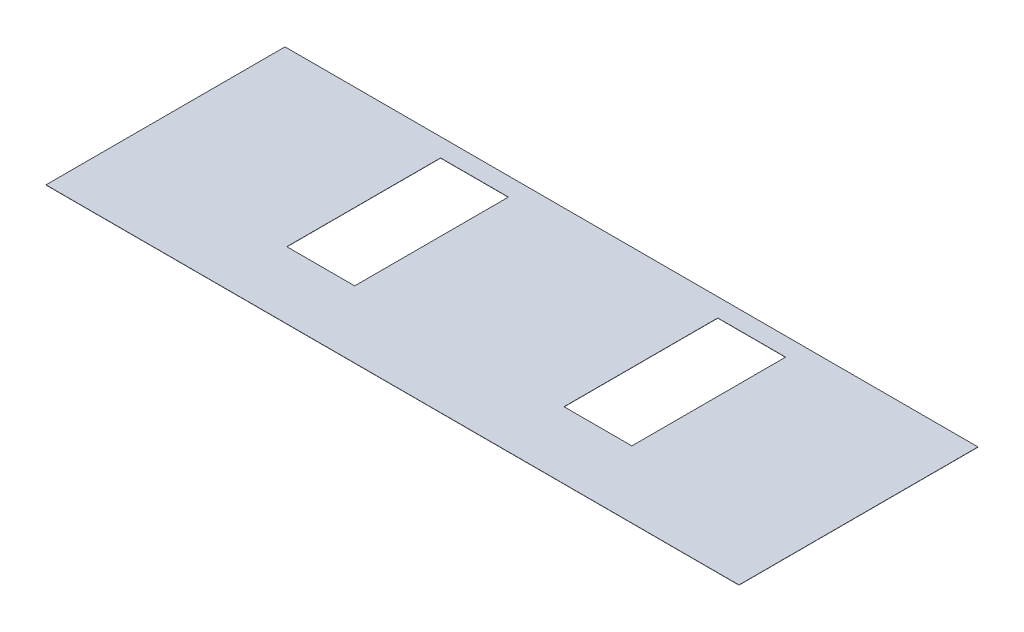
SolidWorks part; units mm, degrees
material "PE High Density Film"
ref_plane "Front Plane" through (0, 0, 0) normal (0, 0, 1) x (1, 0, 0)
ref_plane "Top Plane" through (0, 0, 0) normal (0, 1, 0) x (1, 0, 0)
ref_plane "Right Plane" through (0, 0, 0) normal (1, 0, 0) x (0, 0, -1)
sketch "Sketch1" plane through (0, 0, 0) normal (0, 1, 0) x (1, 0, 0)
  line L1 (-3048, -1051.306) -> (3048, -1051.306)
  line L2 (-3048, -1051.306) -> (-3048, 1051.306)
  line L3 (-3048, 1051.306) -> (3048, 1051.306)
  line L4 (3048, -1051.306) -> (3048, 1051.306)
  line L5 (-3048, -1051.306) -> (3048, 1051.306) construction
  line L6 (-3048, 1051.306) -> (3048, -1051.306) construction
  point P0 (0, 0)
  dimension "D1" = 2102.612
  dimension "D2" = 6096
extrude "Boss-Extrude1" add sketch "Sketch1" along normal blind 1.5875
sketch "Sketch2" plane through (0, 1.5875, 0) normal (0, 1, 0) x (1, 0, 0)
  line L0 (-3048, 1051.306) -> (-1828.8, 1051.306) construction
  line L1 (3048, 1051.306) -> (-3048, 1051.306) construction
  line L2 (-1828.8, 1051.306) -> (-609.6, 1051.306) construction
  line L3 (-609.6, 1051.306) -> (609.6, 1051.306) construction
  line L4 (609.6, 1051.306) -> (1828.8, 1051.306) construction
  line L5 (1828.8, 1051.306) -> (3048, 1051.306) construction
  line L6 (-1219.2, 1051.306) -> (-1219.2, -252.9133) construction
  line L7 (1219.2, 1051.306) -> (1219.2, -252.9133) construction
  line L9 (-1517.65, 889.381) -> (-920.75, 889.381)
  line L10 (-1517.65, 889.381) -> (-1517.65, -463.169)
  line L11 (-1517.65, -463.169) -> (-920.75, -463.169)
  line L12 (-920.75, 889.381) -> (-920.75, -463.169)
  line L13 (-1517.65, 889.381) -> (-920.75, -463.169) construction
  line L14 (-1517.65, -463.169) -> (-920.75, 889.381) construction
  line L15 (920.75, 889.381) -> (1517.65, 889.381)
  line L16 (920.75, 889.381) -> (920.75, -463.169)
  line L17 (920.75, -463.169) -> (1517.65, -463.169)
  line L18 (1517.65, 889.381) -> (1517.65, -463.169)
  line L19 (920.75, 889.381) -> (1517.65, -463.169) construction
  line L20 (920.75, -463.169) -> (1517.65, 889.381) construction
  point P14 (-1219.2, 213.106)
  point P19 (1219.2, 213.106)
  dimension "D1" = 838.2
  dimension "D2" = 1352.55
  dimension "D3" = 596.9
extrude "Cut-Extrude1" cut sketch "Sketch2" against normal through all both and the other way through all
